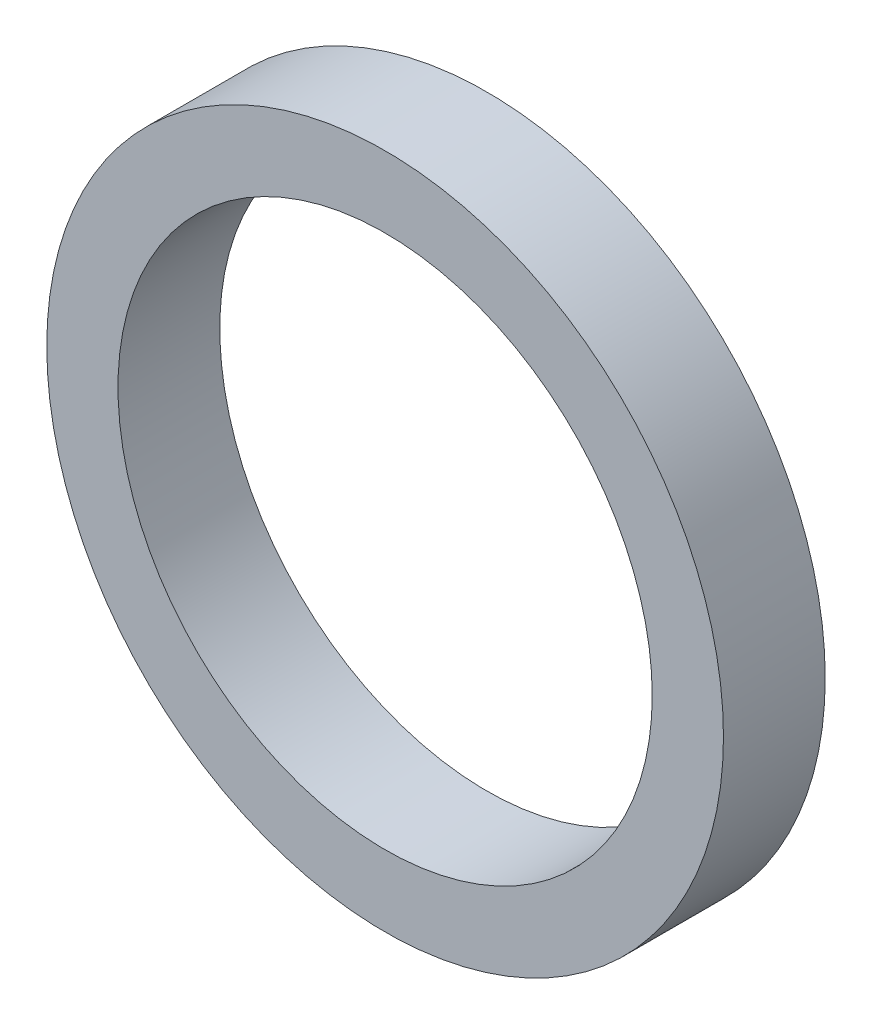
SolidWorks part; units mm, degrees
material "ABS"
ref_plane "Front Plane" through (0, 0, 0) normal (0, 0, 1) x (1, 0, 0)
ref_plane "Top Plane" through (0, 0, 0) normal (0, 1, 0) x (1, 0, 0)
ref_plane "Right Plane" through (0, 0, 0) normal (1, 0, 0) x (0, 0, -1)
sketch "Sketch1" plane through (0, 0, 3) normal (0, 0, 1) x (1, 0, 0)
  circle A0 centre (33, 0) radius 2.625
  circle A1 centre (33, 0) radius 3.325
  dimension "D1" = 5.25
  dimension "D2" = 6.65
extrude "Boss-Extrude1" add sketch "Sketch1" along normal blind 1
equation "\"RingPinShaft\"= 5.05"
equation "\"CenterBearingOut\"=32.05"
equation "\"OutputBearingOut\"=37.05"
equation "\"RingPostIn\"=5.15"
equation "\"CamBearingOut\"=15.1"
equation "\"DiskOutputShaft\"=10.1"
equation "\"CenterShaft\"=25.2"
equation "\"Eccentricity\"=2"
equation "\"CycCamShaft\"=10.05"
equation "\"m3Thru\"=3.15"
equation "\"m3Insert\"=4.2"
equation "\"D1@Sketch1\"=\"RingPostIn\"+0.1"
equation "\"D2@Sketch1\"=\"RingPostIn\"+1.5"
